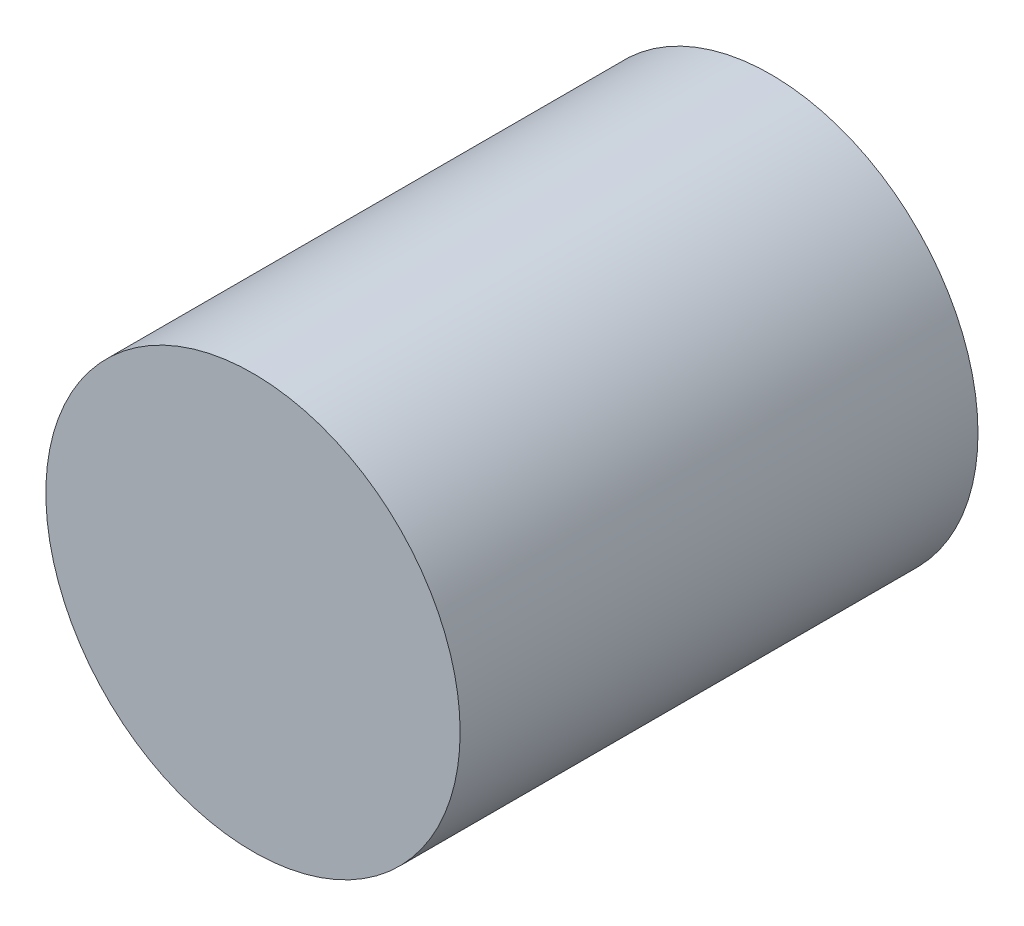
SolidWorks part; units mm, degrees
ref_plane "Front Plane" through (0, 0, 0) normal (0, 0, 1) x (1, 0, 0)
ref_plane "Top Plane" through (0, 0, 0) normal (0, 1, 0) x (1, 0, 0)
ref_plane "Right Plane" through (0, 0, 0) normal (1, 0, 0) x (0, 0, -1)
sketch "Sketch1" plane through (0, 0, 0) normal (0, 1, 0) x (1, 0, 0)
  line L0 (0, 0) -> (0, 25) construction
  line L1 (0, 25) -> (10, 25)
  line L2 (10, 25) -> (10, 0)
  line L3 (10, 0) -> (0, 0)
  line L4 (0, 0) -> (0, 25)
  dimension "D1" = 20
  dimension "D2" = 25
revolve "Revolve1" add sketch "Sketch1" angle 360 about L0
